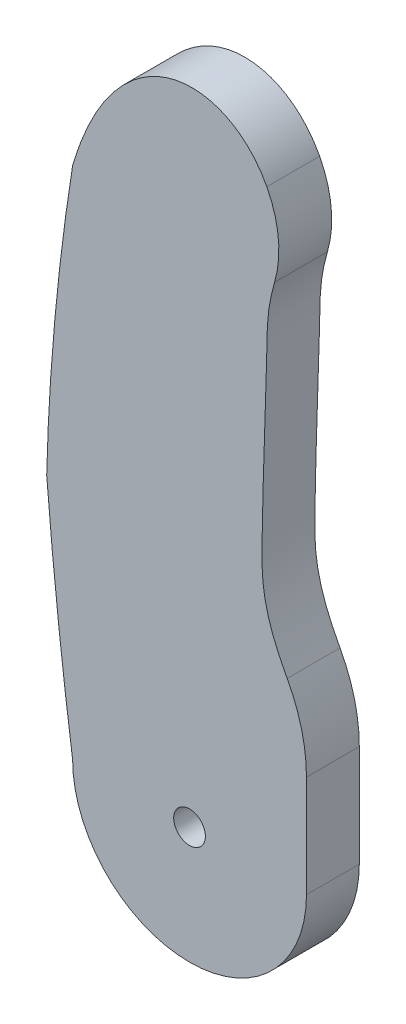
SolidWorks part; units mm, degrees
ref_plane "Front Plane" through (0, 0, 0) normal (0, 0, 1) x (1, 0, 0)
ref_plane "Top Plane" through (0, 0, 0) normal (0, 1, 0) x (1, 0, 0)
ref_plane "Right Plane" through (0, 0, 0) normal (1, 0, 0) x (0, 0, -1)
sketch "Sketch1" plane through (0, 0, 0) normal (0, 0, 1) x (1, 0, 0)
  line L1 (-22.0255, -12.4603) -> (-22.0255, -22.0997)
  arc A0 (-44.1532, -22.0997) -> (-22.0255, -22.0997) centre (-33.0893, -22.0997) ccw
  arc A1 (-25.7774, 34.0422) -> (-25.0423, 26.5822) centre (-34.6362, 29.403) cw
  arc A2 (-23.8518, -5.2872) -> (-22.0255, -12.4603) centre (-37.0255, -12.4603) cw
  spline S0 degree 2 poles (-46.6059, 0) (-46.2587, 13.3745) (-44.1532, 26.5822) knots 0 0 0 1 1 1
  spline S1 degree 3 poles (-44.1532, 26.5822) (-39.9005, 41.1834) (-29.4087, 40.9764) (-25.7774, 34.0422) knots 0 0 0 0 0.860338 0.860338 0.860338 0.860338
  spline S2 degree 3 poles (-25.0423, 26.5822) (-25.76, 24.1412) (-25.7197, 19.5048) (-26.3075, 6.669) (-26.2503, -0.8822) (-23.8518, -5.2872) knots 0.083338 0.083338 0.083338 0.083338 0.311519 0.739397 0.959194 0.959194 0.959194 0.959194
  spline S3 degree 2 poles (-46.6059, 0) (-45.7113, -11.0891) (-44.1532, -22.0997) knots 0 0 0 1 1 1
  point P13 (-44.2548, -13.3304)
  point P15 (-44.9267, -16.3039)
  point P16 (-46.6059, 0)
  point P17 (-26.5816, 4.3329)
  point P18 (-22.0255, -11.8537)
  point P19 (-25.7774, 22.5398)
  point P20 (0, 0)
  point P23 (-25.7901, 20.3139)
  point P24 (-26.2324, 4.4665)
  point P25 (-31.3208, 38.4592)
  point P26 (-23.8518, -5.2872)
  point P27 (0, 0)
  point P28 (-44.1532, 26.5822)
  point P29 (0, 0)
  dimension "D1" = 10
  dimension "D2" = 15
extrude "Boss-Extrude1" add sketch "Sketch1" along normal blind 5
sketch "Sketch2" plane through (0, 0, 5) normal (0, 0, 1) x (1, 0, 0)
  circle A1 centre (-33.0893, -22.0997) radius 1.5
extrude "Cut-Extrude1" cut sketch "Sketch2" against normal blind 15
